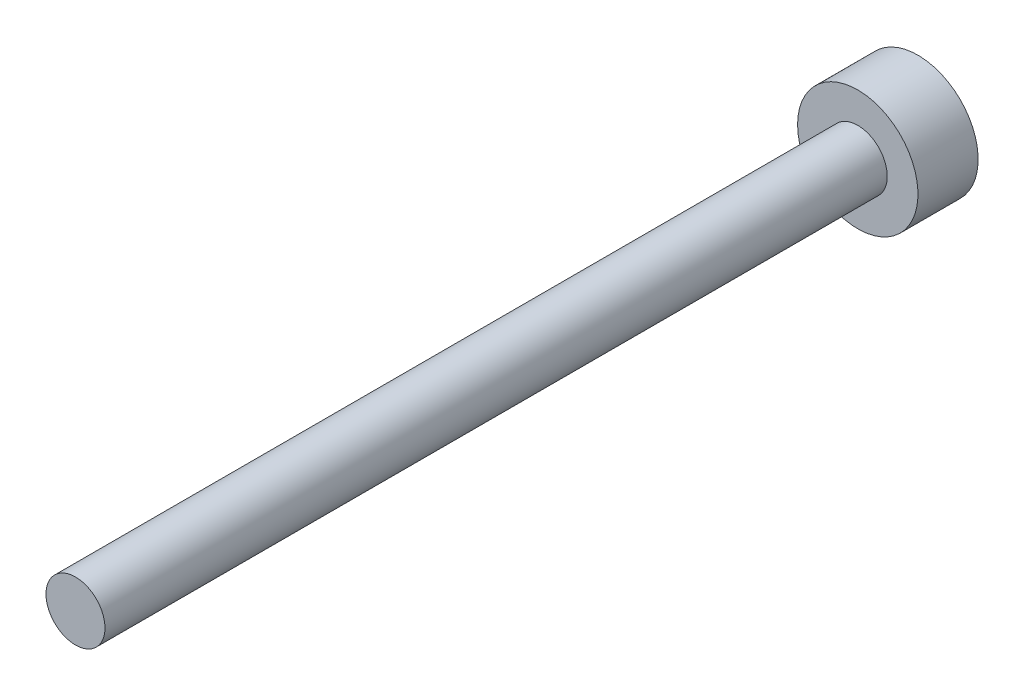
SolidWorks part; units mm, degrees
ref_plane "前视基准面" through (0, 0, 0) normal (0, 0, 1) x (1, 0, 0)
ref_plane "上视基准面" through (0, 0, 0) normal (0, 1, 0) x (1, 0, 0)
ref_plane "右视基准面" through (0, 0, 0) normal (1, 0, 0) x (0, 0, -1)
sketch "草图1" plane through (0, 0, 0) normal (0, 0, 1) x (1, 0, 0)
  circle A0 centre (0, 0) radius 2.45
  dimension "D1" = 4.9
extrude "凸台-拉伸1" add sketch "草图1" along normal blind 70
sketch "草图2" plane through (0, 0, 0) normal (0, 0, -1) x (-1, 0, 0)
  circle A0 centre (0, 0) radius 5
  dimension "D1" = 10
extrude "凸台-拉伸2" add sketch "草图2" against normal blind 5
